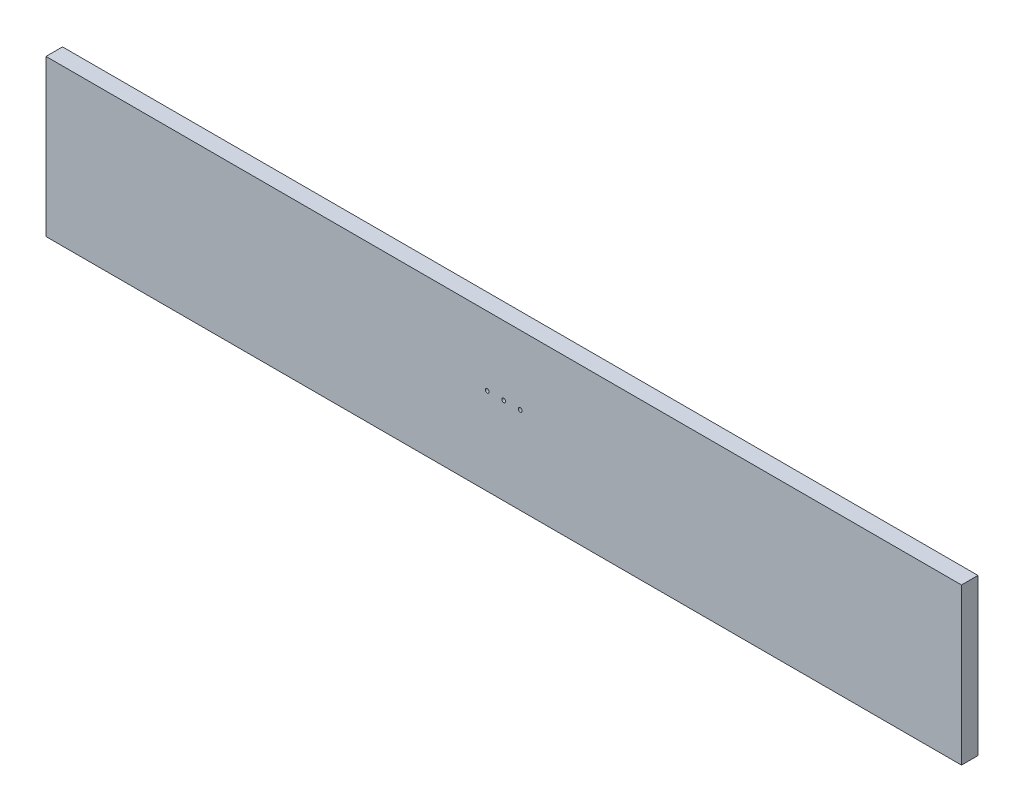
SolidWorks part; units mm, degrees
ref_plane "前视基准面" through (0, 0, 0) normal (0, 0, 1) x (1, 0, 0)
ref_plane "上视基准面" through (0, 0, 0) normal (0, 1, 0) x (1, 0, 0)
ref_plane "右视基准面" through (0, 0, 0) normal (1, 0, 0) x (0, 0, -1)
sketch "草图1" plane through (0, 0, 0) normal (0, 0, 1) x (1, 0, 0)
  line L1 (-352, 60) -> (352, 60)
  line L2 (-352, 60) -> (-352, -60)
  line L3 (-352, -60) -> (352, -60)
  line L4 (352, 60) -> (352, -60)
  line L5 (-352, 60) -> (352, -60) construction
  line L6 (-352, -60) -> (352, 60) construction
  point P0 (0, 0)
  dimension "D1" = 120
  dimension "D2" = 704
extrude "凸台-拉伸1" add sketch "草图1" along normal blind 12.7
sketch "草图2" plane through (0, 0, 12.7) normal (0, 0, 1) x (1, 0, 0)
  line L0 (352, 60) -> (-352, 60) construction
  line L1 (352, -60) -> (352, 60) construction
  circle A0 centre (12.69, 6.92) radius 1.5
  circle A1 centre (-0.01, 6.92) radius 1.5
  circle A2 centre (-12.71, 6.92) radius 1.5
  dimension "D2" = 339.31
  dimension "D3" = 3
  dimension "D1" = 53.08
  dimension "D4" = 3
extrude "切除-拉伸1" cut sketch "草图2" against normal through all
